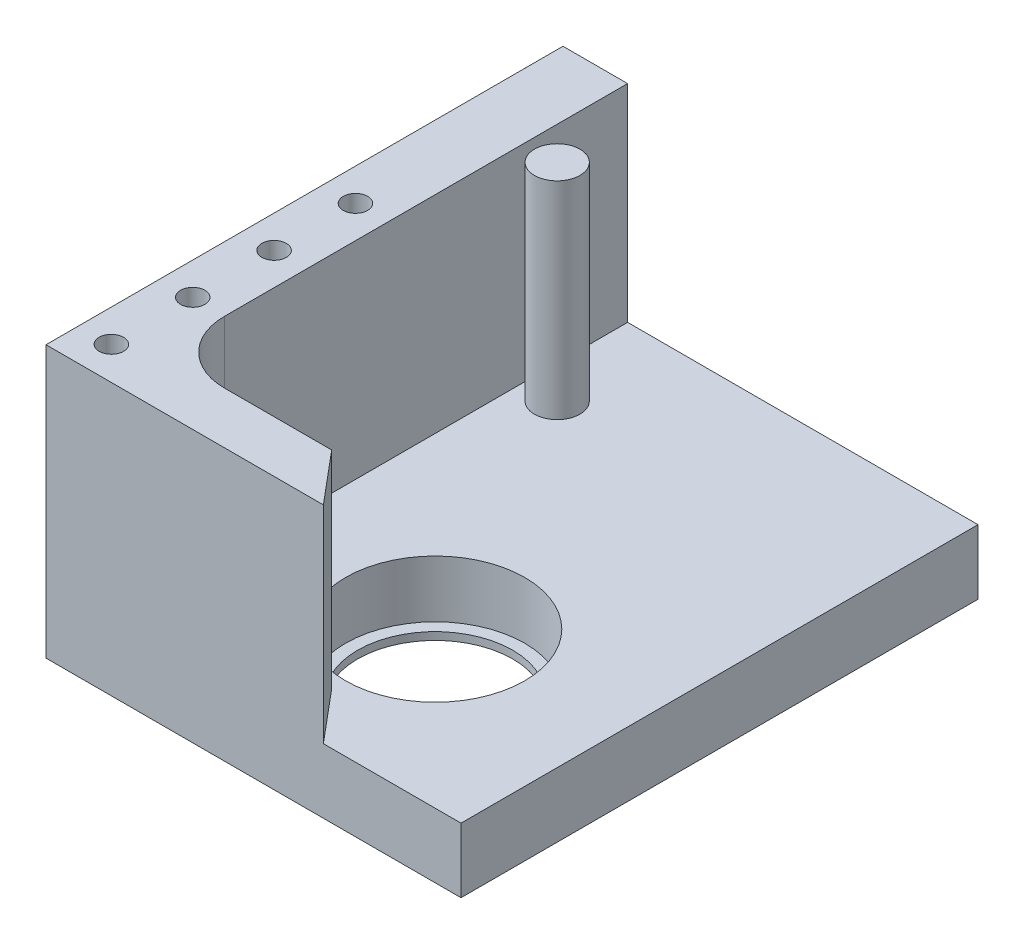
SolidWorks part; units mm, degrees
ref_plane "Front Plane" through (0, 0, 0) normal (0, 0, 1) x (1, 0, 0)
ref_plane "Top Plane" through (0, 0, 0) normal (0, 1, 0) x (1, 0, 0)
ref_plane "Right Plane" through (0, 0, 0) normal (1, 0, 0) x (0, 0, -1)
sketch "Sketch1" plane through (0, 0, 0) normal (0, 1, 0) x (1, 0, 0)
  line L0 (0, 0) -> (22.225, 0) construction
  line L1 (22.225, 19.05) -> (-28.75, 19.05)
  line L2 (22.225, 19.05) -> (22.225, -19.05)
  line L3 (22.225, -19.05) -> (-28.75, -19.05)
  line L4 (-28.75, 19.05) -> (-28.75, -19.05)
  line L5 (15.875, 12.7) -> (-9.525, -12.7) construction
  line L10 (15.875, 12.7) -> (-9.525, 12.7) construction
  line L11 (15.875, 12.7) -> (15.875, -12.7) construction
  line L12 (15.875, -12.7) -> (-9.525, -12.7) construction
  line L13 (-9.525, 12.7) -> (-9.525, -12.7) construction
  line L14 (-34.925, 12.7) -> (-9.525, 12.7) construction
  circle A0 centre (0, 0) radius 11 construction
  point P7 (3.175, 0)
  line B0 (12.875, 6.35) -> (18.875, 6.35)
  line B1 (12.875, 6.35) -> (12.875, 19.05)
  line B2 (12.875, 19.05) -> (18.875, 19.05)
  line B3 (18.875, 6.35) -> (18.875, 19.05)
  line B4 (12.875, 6.35) -> (18.875, 19.05) construction
  line B5 (12.875, 19.05) -> (18.875, 6.35) construction
  line B6 (-12.525, 6.35) -> (-6.525, 6.35)
  line B7 (-12.525, 6.35) -> (-12.525, 19.05)
  line B8 (-6.525, 6.35) -> (-6.525, 19.05)
  line B9 (-12.525, 6.35) -> (-6.525, 19.05) construction
  line B10 (-12.525, 19.05) -> (-6.525, 6.35) construction
  line B11 (-12.525, -19.05) -> (-12.525, -6.35)
  line B12 (-12.525, -6.35) -> (-6.525, -6.35)
  line B13 (-6.525, -19.05) -> (-6.525, -6.35)
  line B14 (-12.525, -19.05) -> (-6.525, -6.35) construction
  line B15 (-12.525, -6.35) -> (-6.525, -19.05) construction
  line B16 (12.875, -19.05) -> (12.875, -6.35)
  line B17 (12.875, -6.35) -> (18.875, -6.35)
  line B18 (18.875, -19.05) -> (18.875, -6.35)
  line B19 (12.875, -19.05) -> (18.875, -6.35) construction
  line B20 (12.875, -6.35) -> (18.875, -19.05) construction
  line B21 (-37.925, 6.35) -> (-31.925, 6.35)
  line B22 (-37.925, 6.35) -> (-37.925, 19.05)
  line B23 (-37.925, 19.05) -> (-31.925, 19.05)
  line B24 (-31.925, 6.35) -> (-31.925, 19.05)
  line B25 (-37.925, 6.35) -> (-31.925, 19.05) construction
  line B26 (-37.925, 19.05) -> (-31.925, 6.35) construction
  line B27 (-37.925, -19.05) -> (-31.925, -19.05)
  line B28 (-37.925, -19.05) -> (-37.925, -6.35)
  line B29 (-37.925, -6.35) -> (-31.925, -6.35)
  line B30 (-31.925, -19.05) -> (-31.925, -6.35)
  line B31 (-37.925, -19.05) -> (-31.925, -6.35) construction
  line B32 (-37.925, -6.35) -> (-31.925, -19.05) construction
  dimension "D2" = 22
  dimension "D1" = 38.1
  dimension "D3" = 25.4
  dimension "D4" = 25.4
  dimension "D5" = 3.175
  dimension "D6" = 22.225
  dimension "D7" = 3.175
sketch_block_instance "SlotGeo-1"
sketch_block "SlotGeo" parameters "D1"=3.1784, "D2"=8.2348
sketch_block_instance "SlotGeo-2"
sketch_block_instance "SlotGeo-3"
sketch_block_instance "SlotGeo-4"
sketch_block_instance "SlotGeo-5"
sketch_block_instance "SlotGeo-6"
extrude "Base" add sketch "Sketch1" along normal blind 7.9375 contours L2 L1 L4 L3
ref_plane "TopBasePlate" through (0, -3.175, 0) normal (0, -1, 0) x (-1, 0, 0)
sketch "Sketch2" plane through (0, 7.9375, 0) normal (0, 1, 0) x (1, 0, 0)
  circle A0 centre (0, 0) radius 11
  dimension "D1" = 22
extrude "Bearing Bore" cut sketch "Sketch2" against normal blind 7 contours A0
sketch "Sketch3" plane through (0, 0.9375, 0) normal (0, 1, 0) x (1, 0, 0)
  circle A0 centre (0, 0) radius 9.525
  dimension "D1" = 19.05
extrude "Thru Hole" cut sketch "Sketch3" against normal through all both and the other way through all
sketch "Sketch4" plane through (0, 7.9375, 0) normal (0, 1, 0) x (1, 0, 0)
  line L0 (22.225, 19.05) -> (-28.75, 19.05) construction
  line L1 (-28.75, -19.05) -> (-20.8125, -19.05)
  line L2 (-28.75, -19.05) -> (-28.75, 19.05)
  line L3 (-28.75, 19.05) -> (-20.8125, 19.05)
  line L4 (-20.8125, -19.05) -> (-20.8125, 19.05)
  dimension "D1" = 7.9375
extrude "Vertical" add sketch "Sketch4" along normal blind 25.4
sketch "Sketch5" plane through (-28.75, 0, 0) normal (-1, 0, 0) x (0, 0, 1)
  line L0 (-12.7, 19.225) -> (12.7, 19.225) construction
  line L1 (12.7, 19.225) -> (12.7, -3.175) construction
  line L3 (-20.955, -3.175) -> (20.955, -3.175) construction
  line L4 (21.5743, -6.175) -> (-23.6916, -6.175) construction
  line L5 (21.5743, -9.175) -> (-23.6916, -9.175) construction
  line L6 (21.5743, -9.175) -> (21.5743, -3.175) construction
  line L7 (21.5743, -3.175) -> (-23.6916, -3.175) construction
  line L8 (-23.6916, -9.175) -> (-23.6916, -3.175) construction
  line B0 (19.05, 16.225) -> (19.05, 22.225)
  line B1 (19.05, 16.225) -> (6.35, 16.225)
  line B2 (6.35, 16.225) -> (6.35, 22.225)
  line B3 (19.05, 22.225) -> (6.35, 22.225)
  line B4 (19.05, 16.225) -> (6.35, 22.225) construction
  line B5 (6.35, 16.225) -> (19.05, 22.225) construction
  line B6 (-6.35, 16.225) -> (-6.35, 22.225)
  line B7 (-6.35, 16.225) -> (-19.05, 16.225)
  line B8 (-6.35, 22.225) -> (-19.05, 22.225)
  line B9 (-6.35, 16.225) -> (-19.05, 22.225) construction
  line B10 (-19.05, 16.225) -> (-6.35, 22.225) construction
  dimension "D1" = 25.4
  dimension "D2" = 6
  dimension "D3" = 25.4
sketch_block_instance "SlotGeo-7"
sketch_block_instance "SlotGeo-8"
sketch "Sketch6" plane through (0, 33.3375, 0) normal (0, 1, 0) x (1, 0, 0)
  line L0 (-24.7812, 14.9904) -> (-24.7812, -14.9904) construction
  line L1 (-28.75, 0) -> (-20.8125, 0) construction
  line L9 (-28.75, 19.05) -> (-28.75, -19.05)
  line L10 (-28.75, -19.05) -> (-20.8125, -19.05)
  line L11 (-20.8125, -19.05) -> (-20.8125, 19.05)
  line L12 (-20.8125, 19.05) -> (-28.75, 19.05)
  line L13 (-28.75, 19.05) -> (-28.75, -19.05) construction
  line L14 (-28.75, -19.05) -> (-20.8125, -19.05) construction
  line L15 (-20.8125, -19.05) -> (-20.8125, 19.05) construction
  line L16 (-20.8125, 19.05) -> (-28.75, 19.05) construction
  circle A0 centre (-24.7812, 14.9904) radius 1.5
  circle A1 centre (-24.7812, 4.9968) radius 1.5
  circle A2 centre (-24.7812, -14.9904) radius 1.5
  circle A3 centre (-24.7812, -4.9968) radius 1.5
  point P6 (-24.7812, 0)
  point P7 (-24.7812, 0)
  dimension "D1" = 3
  dimension "D4" = 3
  dimension "D5" = 3
  dimension "D3" = 29.9808
  dimension "D6" = 9.9936
  dimension "D7" = 19.9872
  dimension "D2" = 0
sketch "Sketch7" plane through (-20.8125, 0, 0) normal (1, 0, 0) x (0, 0, -1)
  line L0 (-19.05, 7.9375) -> (19.05, 7.9375) construction
  line L1 (-19.05, 33.3375) -> (-12.7, 33.3375)
  line L2 (-19.05, 33.3375) -> (-19.05, 7.9375)
  line L3 (-19.05, 7.9375) -> (-12.7, 7.9375)
  line L4 (-12.7, 33.3375) -> (-12.7, 7.9375)
  dimension "D1" = 6.35
extrude "Arm Stop" add sketch "Sketch7" along normal blind 20.8026
sketch "Sketch8" plane through (0, 33.3375, 0) normal (0, 1, 0) x (1, 0, 0)
  line L0 (-0.0099, -12.7) -> (5.3184, -19.05)
  line L1 (22.225, -19.05) -> (-0.0099, -19.05) construction
  line L2 (5.3184, -19.05) -> (-0.0099, -19.05)
  line L3 (-0.0099, -19.05) -> (-0.0099, -12.7)
  dimension "D1" = 40
extrude "Angled Face" add sketch "Sketch8" against normal up to next
fillet "Fillet1" radius 7.62 1 edges at (-20.8125, 20.6375, 12.7)
extrude "Dowel Holes" cut sketch "Sketch6" against normal blind 7.008
sketch "Sketch11" plane through (0, 0, -19.05) normal (0, 0, -1) x (-1, 0, 0)
  line L0 (-22.225, 7.9375) -> (20.8125, 7.9375)
  line L1 (20.8125, 7.9375) -> (20.8125, 33.3375)
  line L2 (20.8125, 33.3375) -> (28.75, 33.3375) construction
  line L3 (20.8125, 33.3375) -> (28.75, 33.3375)
  line L4 (28.75, 33.3375) -> (28.75, 0)
  line L5 (28.75, 0) -> (-22.225, 0)
  line L6 (-22.225, 0) -> (-22.225, 7.9375)
extrude "Spring Base" add sketch "Sketch11" along normal blind 25.4
sketch "Sketch12" plane through (0, 7.9375, 0) normal (0, 1, 0) x (1, 0, 0)
  line L0 (-16.7612, 44.45) -> (-16.7612, 31.75) construction
  line L1 (-20.8125, 44.45) -> (22.225, 44.45) construction
  line L2 (-20.8125, -5.08) -> (-20.8125, 44.45) construction
  circle A0 centre (-16.7612, 31.75) radius 2.794
  dimension "D3" = 5.588
  dimension "D1" = 4.0513
  dimension "D2" = 12.7
extrude "Spring Mount" add sketch "Sketch12" along normal blind 25.4 contours A0
equation "\"D4@Sketch6\"=\"D1@Sketch6\""
equation "\"D5@Sketch6\"=\"D1@Sketch6\""
equation "\"D6@Sketch6\"=\"D3@Sketch6\"/3"
equation "\"D7@Sketch6\"=2*\"D3@Sketch6\"/3"
